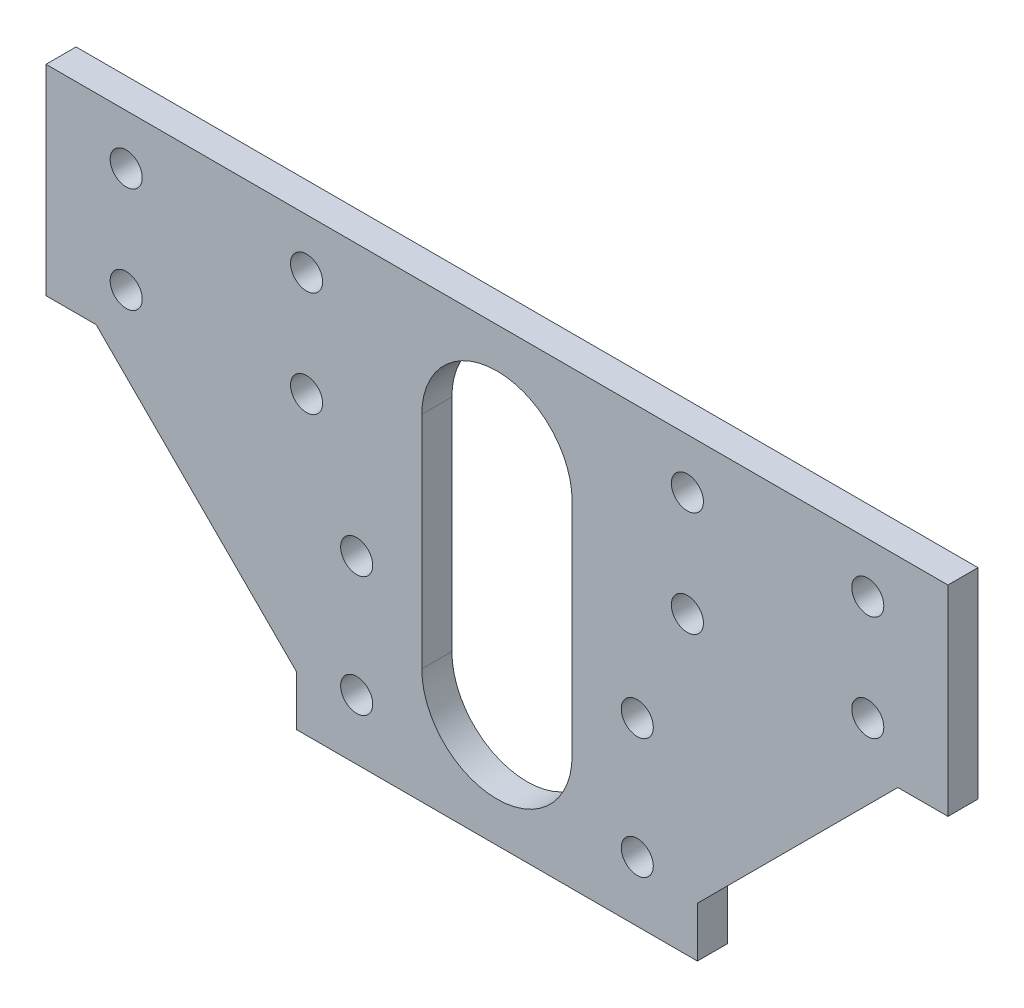
SolidWorks part; units mm, degrees
material "Thornel VCB-20 碳布"
ref_plane "前视基准面" through (0, 0, 0) normal (0, 0, 1) x (1, 0, 0)
ref_plane "上视基准面" through (0, 0, 0) normal (0, 1, 0) x (1, 0, 0)
ref_plane "右视基准面" through (0, 0, 0) normal (1, 0, 0) x (0, 0, -1)
other "Configuration Table"
sketch "草图1" plane through (0, 0, 0) normal (0, 0, 1) x (1, 0, 0)
  line L0 (0, 0) -> (90, 0)
  line L1 (90, 0) -> (90, -20)
  line L2 (90, -20) -> (85, -20)
  line L3 (85, -20) -> (65, -40)
  line L4 (65, -40) -> (65, -45)
  line L5 (65, -45) -> (25, -45)
  line L6 (25, -45) -> (25, -40)
  line L7 (25, -40) -> (5, -20)
  line L8 (5, -20) -> (0, -20)
  line L9 (0, -20) -> (0, 0)
  line L10 (5, -20) -> (85, -20) construction
  line L11 (65, -40) -> (65, -20) construction
  line L12 (25, -40) -> (25, -20) construction
  dimension "D1" = 40
  dimension "D2" = 20
  dimension "D3" = 45
  dimension "D4" = 25
  dimension "D5" = 25
  dimension "D6" = 25
  dimension "D7" = 20
extrude "凸台-拉伸1" add sketch "草图1" along normal blind 3
sketch "草图2" plane through (0, 0, 3) normal (0, 0, 1) x (1, 0, 0)
  line L0 (45, -11.5) -> (45, -33.5) construction
  line L1 (8, -5) -> (82, -5) construction
  line L2 (8, -5) -> (8, -15.5) construction
  line L3 (8, -15.5) -> (82, -15.5) construction
  line L4 (82, -5) -> (82, -15.5) construction
  line L5 (31, -27) -> (59, -27) construction
  line L6 (31, -27) -> (31, -39) construction
  line L7 (31, -39) -> (59, -39) construction
  line L8 (59, -27) -> (59, -39) construction
  line L9 (52.5, -11.5) -> (52.5, -33.5)
  line L10 (0, 0) -> (0, -20)
  line L11 (0, -20) -> (5, -20)
  line L12 (5, -20) -> (25, -40)
  line L13 (25, -40) -> (25, -45)
  line L14 (25, -45) -> (65, -45)
  line L15 (65, -45) -> (65, -40)
  line L16 (65, -40) -> (85, -20)
  line L17 (85, -20) -> (90, -20)
  line L18 (90, -20) -> (90, 0)
  line L19 (90, 0) -> (0, 0)
  line L20 (0, 0) -> (0, -20) construction
  line L21 (0, -20) -> (5, -20) construction
  line L22 (5, -20) -> (25, -40) construction
  line L23 (25, -40) -> (25, -45) construction
  line L24 (25, -45) -> (65, -45) construction
  line L25 (65, -45) -> (65, -40) construction
  line L26 (65, -40) -> (85, -20) construction
  line L27 (85, -20) -> (90, -20) construction
  line L28 (90, -20) -> (90, 0) construction
  line L29 (90, 0) -> (0, 0) construction
  line L30 (37.5, -11.5) -> (37.5, -33.5)
  circle A0 centre (82, -5) radius 1.6
  circle A1 centre (82, -15.5) radius 1.6
  circle A2 centre (64, -15.5) radius 1.6
  circle A3 centre (64, -5) radius 1.6
  circle A4 centre (26, -5) radius 1.6
  circle A5 centre (26, -15.5) radius 1.6
  circle A6 centre (8, -5) radius 1.6
  circle A7 centre (8, -15.5) radius 1.6
  circle A8 centre (31, -27) radius 1.6
  circle A9 centre (31, -39) radius 1.6
  circle A10 centre (59, -27) radius 1.6
  circle A11 centre (59, -39) radius 1.6
  arc A12 (52.5, -11.5) -> (37.5, -11.5) centre (45, -11.5) ccw
  arc A13 (37.5, -33.5) -> (52.5, -33.5) centre (45, -33.5) ccw
  point P36 (45, -22.5)
  dimension "D2" = 3.2
  dimension "D16" = 7.5
  dimension "D3" = 8
  dimension "D4" = 8
  dimension "D5" = 18
  dimension "D6" = 18
  dimension "D7" = 18
  dimension "D8" = 18
  dimension "D9" = 5
  dimension "D10" = 10.5
  dimension "D11" = 6
  dimension "D12" = 6
  dimension "D13" = 6
  dimension "D14" = 12
  dimension "D15" = 20
  dimension "D17" = 23
  dimension "D18" = 22
  dimension "D1" = 0
extrude "切除-拉伸1" cut sketch "草图2" against normal blind 3
